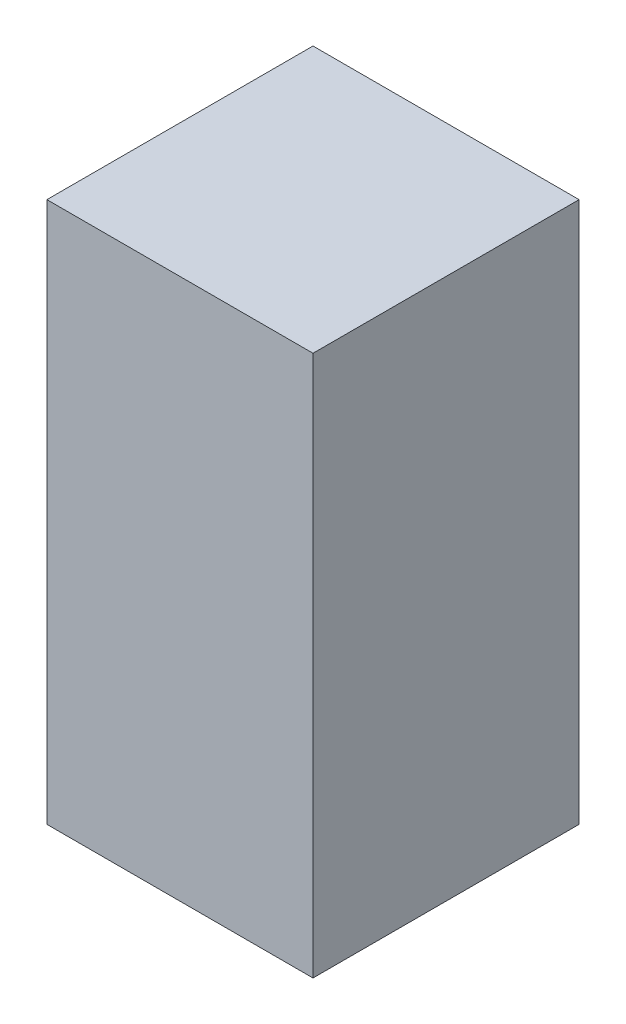
SolidWorks part; units mm, degrees
ref_plane "Front Plane" through (0, 0, 0) normal (0, 0, 1) x (1, 0, 0)
ref_plane "Top Plane" through (0, 0, 0) normal (0, 1, 0) x (1, 0, 0)
ref_plane "Right Plane" through (0, 0, 0) normal (1, 0, 0) x (0, 0, -1)
sketch "Sketch1" plane through (0, 0, 0) normal (0, 1, 0) x (1, 0, 0)
  line L0 (-150, -150) -> (150, -150)
  line L1 (-150, -150) -> (-150, 150)
  line L2 (150, -150) -> (150, 150)
  line L3 (-150, 150) -> (150, 150)
  line L4 (-150, -150) -> (150, 150) construction
  line L5 (150, -150) -> (-150, 150) construction
  point P2 (0, 0)
  dimension "D1" = 300
  dimension "D2" = 300
extrude "Boss-Extrude1" add sketch "Sketch1" along normal blind 610 contours L1 L3 L2 L0
